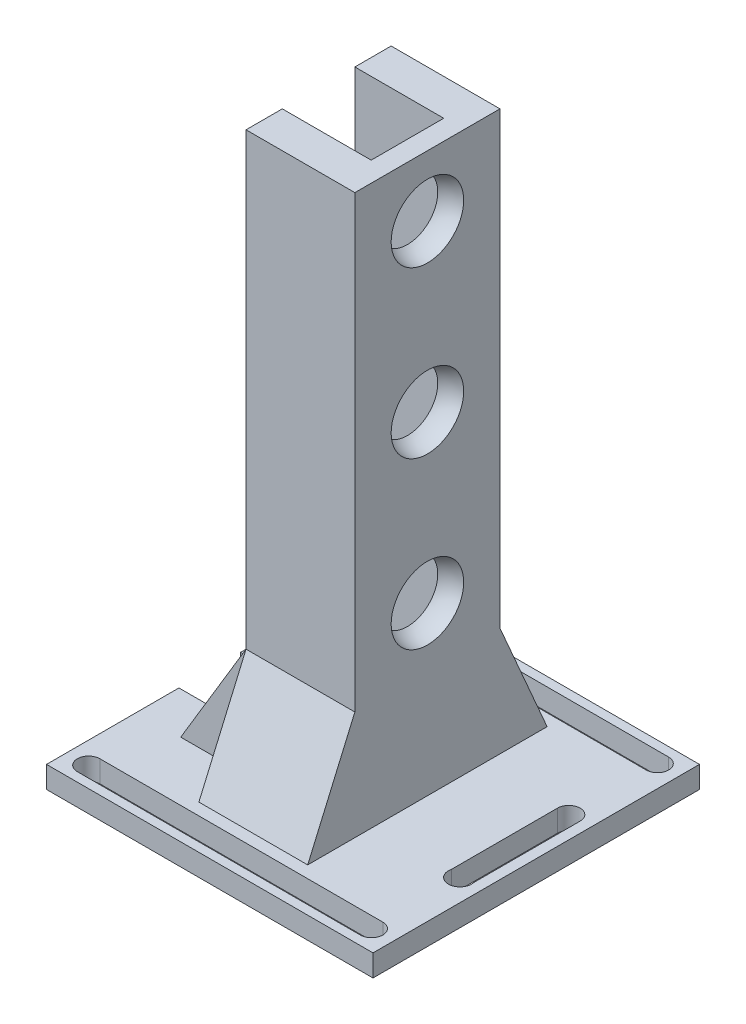
SolidWorks part; units mm, degrees
ref_plane "前视基准面" through (0, 0, 0) normal (0, 0, 1) x (1, 0, 0)
ref_plane "上视基准面" through (0, 0, 0) normal (0, 1, 0) x (1, 0, 0)
ref_plane "右视基准面" through (0, 0, 0) normal (1, 0, 0) x (0, 0, -1)
other "Configuration Table"
sketch "草图1" plane through (0, 0, 0) normal (0, 1, 0) x (1, 0, 0)
  line L1 (-45, 45) -> (45, 45)
  line L2 (-45, 45) -> (-45, -45)
  line L3 (-45, -45) -> (45, -45)
  line L4 (45, 45) -> (45, -45)
  line L5 (-45, 45) -> (45, -45) construction
  line L6 (-45, -45) -> (45, 45) construction
  point P0 (0, 0)
  dimension "D1" = 90
  dimension "D2" = 90
extrude "凸台-拉伸1" add sketch "草图1" along normal blind 6
sketch "草图2" plane through (0, 0, 0) normal (0, 1, 0) x (1, 0, 0)
  line L1 (-15, 20) -> (15, 20)
  line L2 (-15, 20) -> (-15, -20)
  line L3 (-15, -20) -> (15, -20)
  line L4 (15, 20) -> (15, -20)
  line L5 (-15, 20) -> (15, -20) construction
  line L6 (-15, -20) -> (15, 20) construction
  point P0 (0, 0)
  dimension "D1" = 30
  dimension "D2" = 40
extrude "凸台-拉伸2" add sketch "草图2" along normal blind 160
sketch "草图7" plane through (0, 0, 0) normal (0, 0, 1) x (1, 0, 0)
  line L0 (-15, 36) -> (-33, 6)
  line L1 (-15, 160) -> (-15, 6) construction
  line L2 (-45, 6) -> (45, 6) construction
  line L3 (-33, 6) -> (-15, 6)
  line L4 (-15, 6) -> (-15, 36)
  dimension "D1" = 18
  dimension "D2" = 30
extrude "凸台-拉伸3" add sketch "草图7" along normal up to surface and the other way up to surface up to face at (0, 83, 20) other way up to face at (0, 83, -20)
sketch "草图8" plane through (0, 0, 0) normal (0, 1, 0) x (1, 0, 0)
  line L0 (45, 45) -> (-45, 45) construction
  line L1 (-45, 45) -> (-45, -45) construction
  circle A0 centre (-39, 39.4) radius 3.1
  dimension "D2" = 6.2
  dimension "D1" = 5.6
  dimension "D3" = 6
extrude "切除-拉伸2" cut sketch "草图8" along normal up to surface (6 mm away) up to face at (0, 6, 0)
sketch "草图12" plane through (0, 0, 0) normal (0, 0, 1) x (1, 0, 0)
  line L0 (15, 160) -> (15, 6) construction
  line L1 (15, 62) -> (15, 42)
  line L2 (-45, 0) -> (45, 0) construction
  arc A0 (15, 62) -> (15, 42) centre (15, 52) ccw
  dimension "D1" = 10
  dimension "D2" = 52
revolve "切除-旋转2" cut sketch "草图12" angle 360 about L1
pattern_linear "阵列(线性)1" count 3 spacing 45.6 along (0, 1, 0) of "切除-旋转2"
sketch "草图15" plane through (0, 0, 0) normal (1, 0, 0) x (0, 0, -1)
  line L1 (-20, 36) -> (-20, 6)
  line L2 (-20, 6) -> (-33, 6)
  line L7 (-20, 160) -> (-20, 6) construction
  line L10 (-18.2, 6) -> (-43, 6) construction
  line L11 (-33, 6) -> (-20, 36)
extrude "凸台-拉伸4" add sketch "草图15" along normal blind 15 and the other way blind 15
mirror "镜向11" about plane through (0, 0, 0) normal (0, 0, 1) of "凸台-拉伸4"
sketch "草图17" plane through (0, 0, 0) normal (1, 0, 0) x (0, 0, -1)
  line L0 (-20, 160) -> (-20, 36) construction
  line L1 (10, 160) -> (-10, 160)
  line L2 (10, 160) -> (10, 6)
  line L3 (10, 6) -> (-10, 6)
  line L4 (-10, 160) -> (-10, 6)
  line L5 (20, 160) -> (20, 36) construction
  line L6 (33, 6) -> (-33, 6) construction
  line L7 (-20, 160) -> (20, 160) construction
  line L8 (-45, 0) -> (45, 0) construction
  dimension "D1" = 20
  dimension "D2" = 10
  dimension "D3" = 10
  dimension "D4" = 0
  dimension "D5" = 0
  dimension "D6" = 154
  dimension "D7" = 6
extrude "切除-拉伸4" cut sketch "草图17" against normal through all and the other way blind 9.5
sketch "草图21" plane through (0, 0, 0) normal (1, 0, 0) x (0, 0, -1)
  line L0 (-8.5, 6) -> (8.5, 6)
  line L1 (33, 6) -> (-33, 6) construction
  line L2 (8.5, 6) -> (8.5, 0)
  line L3 (-45, 0) -> (45, 0) construction
  line L4 (8.5, 0) -> (-8.5, 0)
  line L5 (-8.5, 0) -> (-8.5, 6)
  line L6 (-20, 160) -> (-20, 36) construction
  line L7 (20, 160) -> (20, 36) construction
  dimension "D1" = 17
  dimension "D2" = 11.5
  dimension "D3" = 11.5
extrude "切除-拉伸8" cut sketch "草图21" against normal through all and the other way blind 9.5
mirror "镜向12" about plane through (0, 0, 0) normal (1, 0, 0) of "切除-拉伸2"
sketch "草图23" plane through (0, 0, 0) normal (0, 1, 0) x (1, 0, 0)
  line L0 (-39, 42.5) -> (39, 42.5)
  line L1 (39, 42.5) -> (39, 36.3)
  line L2 (39, 36.3) -> (-39, 36.3)
  line L3 (-39, 36.3) -> (-39, 42.5)
  circle A0 centre (-39, 39.4) radius 3.1 construction
  circle A1 centre (39, 39.4) radius 3.1 construction
extrude "切除-拉伸9" cut sketch "草图23" along normal through all
mirror "镜向13" about plane through (0, 0, 0) normal (0, 0, 1) of "切除-拉伸9"
mirror "镜向14" about plane through (0, 0, 0) normal (0, 0, 1) of "镜向12", "切除-拉伸2"
sketch "草图25" plane through (0, 0, 0) normal (0, 1, 0) x (1, 0, 0)
  line L0 (42.1, 15) -> (42.1, -15)
  line L1 (42.1, -15) -> (35.8707, -15)
  line L2 (35.8707, -15) -> (35.8707, 15)
  line L3 (35.8707, 15) -> (42.1, 15)
  line L4 (-45, -45) -> (45, -45) construction
  dimension "D1" = 30
  dimension "D2" = 30
extrude "切除-拉伸10" cut sketch "草图25" along normal through all
sketch "草图26" plane through (0, 0, 0) normal (0, 1, 0) x (1, 0, 0)
  line L0 (35.8707, 15) -> (42.1, 15) construction
  circle A0 centre (38.9854, 15) radius 3.1146
extrude "切除-拉伸11" cut sketch "草图26" along normal through all
sketch "草图27" plane through (0, 0, 0) normal (0, 1, 0) x (1, 0, 0)
  line L0 (42.1, -15) -> (35.8707, -15) construction
  circle A0 centre (38.9854, -15) radius 3.2023
extrude "切除-拉伸12" cut sketch "草图27" along normal through all
